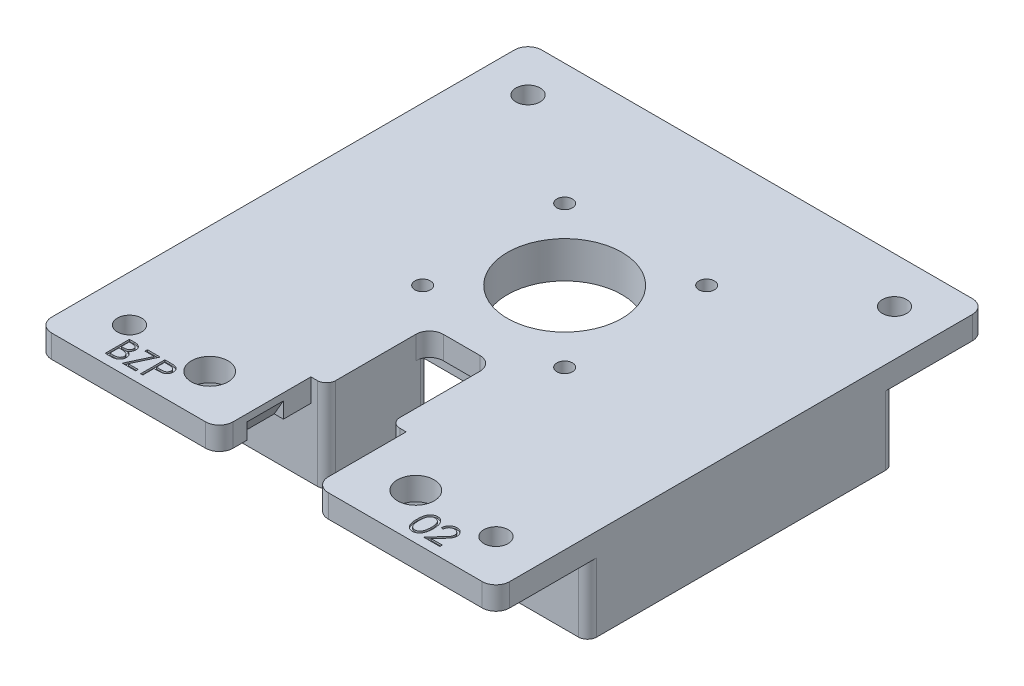
SolidWorks part; units mm, degrees
ref_plane "Front" through (0, 0, 0) normal (0, 0, 1) x (1, 0, 0)
ref_plane "Top" through (0, 0, 0) normal (0, 1, 0) x (1, 0, 0)
ref_plane "Right" through (0, 0, 0) normal (1, 0, 0) x (0, 0, -1)
sketch "Sketch2" plane through (0, 0, 0) normal (0, 1, 0) x (1, 0, 0)
  line L1 (0, 0) -> (100, 0)
  line L2 (0, 0) -> (0, 107)
  line L3 (0, 107) -> (100, 107)
  line L4 (100, 0) -> (100, 107)
  dimension "D1" = 107
  dimension "D2" = 100
extrude "Boss-Extrude1" add sketch "Sketch2" along normal blind 5
sketch "Sketch3" plane through (0, 5, 0) normal (0, 1, 0) x (1, 0, 0)
  line L0 (39.6, 0) -> (39.6, 20)
  line L1 (0, 0) -> (100, 0) construction
  line L2 (39.6, 20) -> (43, 20)
  line L3 (43, 20) -> (43, 42.5)
  line L4 (43, 42.5) -> (57, 42.5)
  line L5 (57, 42.5) -> (57, 20)
  line L6 (57, 20) -> (60.4, 20)
  line L7 (60.4, 20) -> (60.4, 0)
  line L8 (60.4, 0) -> (39.6, 0)
  line L9 (50, 107) -> (50, 65) construction
  line L10 (100, 107) -> (0, 107) construction
  line L11 (43, 42.5) -> (27.5, 42.5) construction
  line L12 (27.5, 87.5) -> (72.5, 87.5) construction
  line L13 (27.5, 87.5) -> (27.5, 42.5) construction
  line L14 (34.5, 49.5) -> (65.5, 49.5) construction
  line L15 (34.5, 49.5) -> (34.5, 80.5) construction
  line L16 (34.5, 80.5) -> (65.5, 80.5) construction
  line L17 (65.5, 49.5) -> (65.5, 80.5) construction
  line L18 (34.5, 49.5) -> (65.5, 80.5) construction
  line L19 (34.5, 80.5) -> (65.5, 49.5) construction
  line L20 (27.5, 42.5) -> (72.5, 42.5) construction
  line L21 (72.5, 87.5) -> (72.5, 42.5) construction
  line L22 (27.5, 87.5) -> (72.5, 42.5) construction
  line L23 (27.5, 42.5) -> (72.5, 87.5) construction
  line L24 (57, 42.5) -> (72.5, 42.5) construction
  line L25 (40, 10) -> (27.5, 10) construction
  line L26 (75, 47) -> (25, 47) construction
  line L27 (75, 47) -> (75, 83) construction
  line L28 (75, 83) -> (25, 83) construction
  line L29 (25, 47) -> (25, 83) construction
  line L30 (75, 47) -> (25, 83) construction
  line L31 (75, 83) -> (25, 47) construction
  line L32 (50, 65) -> (50, 10) construction
  line L33 (40, 0) -> (60, 0) construction
  line L34 (40, 0) -> (40, 20) construction
  line L35 (40, 20) -> (60, 20) construction
  line L36 (60, 0) -> (60, 20) construction
  line L37 (40, 0) -> (60, 20) construction
  line L38 (40, 20) -> (60, 0) construction
  circle A0 centre (50, 65) radius 12.5
  circle A1 centre (65.5, 49.5) radius 1.7
  circle A2 centre (34.5, 49.5) radius 1.7
  circle A3 centre (65.5, 80.5) radius 1.7
  circle A4 centre (34.5, 80.5) radius 1.7
  circle A5 centre (25, 83) radius 1.7 construction
  circle A6 centre (25, 47) radius 1.7 construction
  circle A7 centre (75, 47) radius 1.7 construction
  circle A8 centre (75, 83) radius 1.7 construction
  circle A9 centre (27.5, 10) radius 4
  circle A10 centre (72.5, 10) radius 4
  point P11 (50, 0)
  point P12 (50, 0)
  point P42 (50, 10)
  dimension "D4" = 25
  dimension "D6" = 3.4
  dimension "D10" = 3.4
  dimension "D12" = 8
  dimension "D2" = 14
  dimension "D3" = 20.8
  dimension "D5" = 31
  dimension "D7" = 42
  dimension "D8" = 50
  dimension "D9" = 36
  dimension "D11" = 45
  dimension "D13" = 20
  dimension "D14" = 12.5
  dimension "D15" = 20
extrude "Cut-Extrude1" cut sketch "Sketch3" against normal blind 20 and the other way through all
sketch "Sketch12" plane through (0, 0, 0) normal (0, -1, 0) x (1, 0, 0)
  line L1 (71.15, -86.15) -> (28.85, -86.15)
  line L2 (71.15, -86.15) -> (71.15, -43.85)
  line L3 (71.15, -43.85) -> (28.85, -43.85)
  line L4 (28.85, -86.15) -> (28.85, -43.85)
  line L5 (71.15, -86.15) -> (28.85, -43.85) construction
  line L6 (71.15, -43.85) -> (28.85, -86.15) construction
  point P0 (50, -65)
  dimension "D1" = 42.3
  dimension "D2" = 42.3
extrude "Boss-Extrude3" add sketch "Sketch12" along normal blind 3
hole_wizard "M5 Clearance Hole1" positions "Sketch6" profile "Sketch5" hole size "M5" standard "ANSI Metric" end condition through all
sketch "Sketch6" plane through (0, 5, 0) normal (0, 1, 0) x (1, 0, 0)
  line L0 (0, 97) -> (100, 97) construction
  line L1 (0, 107) -> (0, 0) construction
  line L2 (100, 0) -> (100, 107) construction
  line L5 (10, 107) -> (10, 0) construction
  line L6 (100, 107) -> (0, 107) construction
  line L7 (0, 0) -> (39.6, 0) construction
  line L10 (90, 107) -> (90, 0) construction
  line L11 (60.4, 0) -> (100, 0) construction
  line L14 (0, 10) -> (100, 10) construction
  point P0 (10, 97)
  point P2 (10, 10)
  point P4 (90, 10)
  point P6 (90, 97)
  dimension "D1" = 10
  dimension "D2" = 10
  dimension "D3" = 10
  dimension "D4" = 10
sketch "Sketch5" plane through (10, 5, -97) normal (1, 0, 0) x (0, 0, 1)
  line L0 (0, 0) -> (0, 8)
  line L1 (0, 8) -> (2.65, 8)
  line L2 (2.65, 8) -> (2.65, 0)
  line L5 (2.65, 0) -> (0, 0)
  line L11 (0, -6.35) -> (0, 107.95) construction
  dimension "Thru Hole Dia." = 5.3
  dimension "Thru Hole Depth" = 8
fillet "Fillet1" radius 3 8 edges at (60.4, 2.5, 0) (39.6, 2.5, 0) (0, 2.5, -107) (100, 2.5, -107) (100, 2.5, 0) (0, 2.5, 0) (57, 2.5, -42.5) (43, 2.5, -42.5)
sketch "Sketch7" plane through (0, 0, 0) normal (0, -1, 0) x (1, 0, 0)
  line L0 (57, -20) -> (100, -20)
  line L1 (100, -3) -> (100, -104) construction
  line L2 (100, -20) -> (100, -87)
  line L3 (100, -87) -> (84, -87)
  line L4 (84, -87) -> (84, -82)
  line L5 (84, -82) -> (95, -82)
  line L6 (95, -82) -> (95, -25)
  line L7 (95, -25) -> (57, -25) construction
  line L8 (57, -25) -> (57, -20)
  line L9 (63.4, 0) -> (97, 0) construction
  line L10 (57, -20) -> (57, -39.5) construction
  line L11 (97, -107) -> (3, -107) construction
  line L12 (50, -107) -> (50, -46.1063) construction
  line L13 (43, -25) -> (43, -20)
  line L14 (5, -25) -> (43, -25) construction
  line L15 (5, -82) -> (5, -25)
  line L16 (16, -82) -> (5, -82)
  line L17 (16, -87) -> (16, -82)
  line L18 (0, -87) -> (16, -87)
  line L19 (0, -20) -> (0, -87)
  line L20 (43, -20) -> (0, -20)
  line L21 (57, -25) -> (57, -42.5)
  line L23 (57, -42.5) -> (62, -42.5)
  line L25 (62, -42.5) -> (62, -25)
  line L26 (62, -25) -> (95, -25)
  line L27 (38, -25) -> (5, -25)
  line L28 (38, -42.5) -> (38, -25)
  line L29 (43, -25) -> (43, -42.5)
  line L31 (43, -42.5) -> (38, -42.5)
  line L32 (54, -42.5) -> (46, -42.5) construction
  dimension "D1" = 20
  dimension "D2" = 20
  dimension "D3" = 16
  dimension "D4" = 5
  dimension "D5" = 5
extrude "Boss-Extrude2" add sketch "Sketch7" along normal blind 15
fillet "Fillet3" radius 3 6 edges at (5, -7.5, -82) (95, -7.5, -82) (5, -7.5, -25) (38, -7.5, -25) (95, -7.5, -25) (62, -7.5, -25)
fillet "Fillet4" radius 2 14 edges at (100, -7.5, -87) (100, -7.5, -20) (43, -5, -20) (57, -5, -20) (84, -7.5, -87) (84, -7.5, -82) (0, -7.5, -20) (0, -7.5, -87) (16, -7.5, -87) (16, -7.5, -82) (38, -7.5, -42.5) (62, -7.5, -42.5) (57, -7.5, -42.5) (43, -7.5, -42.5)
ref_plane "Plane1" through (0, 0, -10) normal (0, 0, 1) x (1, 0, 0)
sketch "Sketch9" plane through (0, 0, -10) normal (0, 0, 1) x (1, 0, 0)
  line L0 (39.6, 0) -> (39.6, 3.4641)
  line L2 (39.6, 0) -> (39.6, 5) construction
  line L3 (39.6, 3.4641) -> (37.6, 0)
  line L4 (37.6, 0) -> (39.6, 0)
  line L5 (60.4, 0) -> (62.4, 0)
  line L6 (98, 0) -> (60.4, 0) construction
  line L7 (62.4, 0) -> (60.4, 3.4641)
  line L8 (60.4, 0) -> (60.4, 5) construction
  line L9 (60.4, 3.4641) -> (60.4, 0)
  dimension "D1" = 30
  dimension "D2" = 2
extrude "Cut-Extrude2" cut sketch "Sketch9" against normal blind 4 and the other way blind 4
sketch "Sketch10" plane through (0, 5, 0) normal (0, 1, 0) x (1, 0, 0)
  line L0 (0, 2) -> (36.1, 2) construction
  line L1 (0, 104) -> (0, 3) construction
  line L3 (3, 0) -> (36.6, 0) construction
  line L4 (39.6, 3) -> (39.6, 20) construction
  text T0 "BZP" font "Century Gothic" height in points 20
  dimension "D1" = 2
  dimension "D2" = 3.5
extrude "Cut-Extrude3" cut sketch "Sketch10" against normal blind 0.4
sketch "Sketch11" plane through (0, 5, 0) normal (0, 1, 0) x (1, 0, 0)
  line L0 (63.9, 2) -> (100, 2) construction
  line L2 (100, 3) -> (100, 104) construction
  line L3 (63.4, 0) -> (97, 0) construction
  line L4 (60.4, 20) -> (60.4, 3) construction
  text T0 "02" font "Century Gothic" height in points 20
  dimension "D1" = 2
  dimension "D2" = 3.5
extrude "Cut-Extrude4" cut sketch "Sketch11" against normal blind 0.4
sketch "Sketch13" plane through (0, 0, 0) normal (0, 1, 0) x (1, 0, 0)
  circle A1 centre (34.5, 80.5) radius 1.7
  circle A2 centre (34.5, 80.5) radius 1.7
  circle A3 centre (65.5, 80.5) radius 1.7
  circle A4 centre (65.5, 80.5) radius 1.7
  circle A5 centre (65.5, 49.5) radius 1.7
  circle A6 centre (65.5, 49.5) radius 1.7
  circle A7 centre (34.5, 49.5) radius 1.7
  circle A8 centre (34.5, 49.5) radius 1.7
  circle A9 centre (50, 65) radius 12.5
  circle A10 centre (50, 65) radius 12.5
  dimension "D1" = 0
  dimension "D2" = 0
  dimension "D3" = 0
  dimension "D4" = 0
  dimension "D5" = 0
extrude "Cut-Extrude5" cut sketch "Sketch13" against normal blind 3
equation "\"D5@Sketch7\"=\"D4@Sketch7\""
